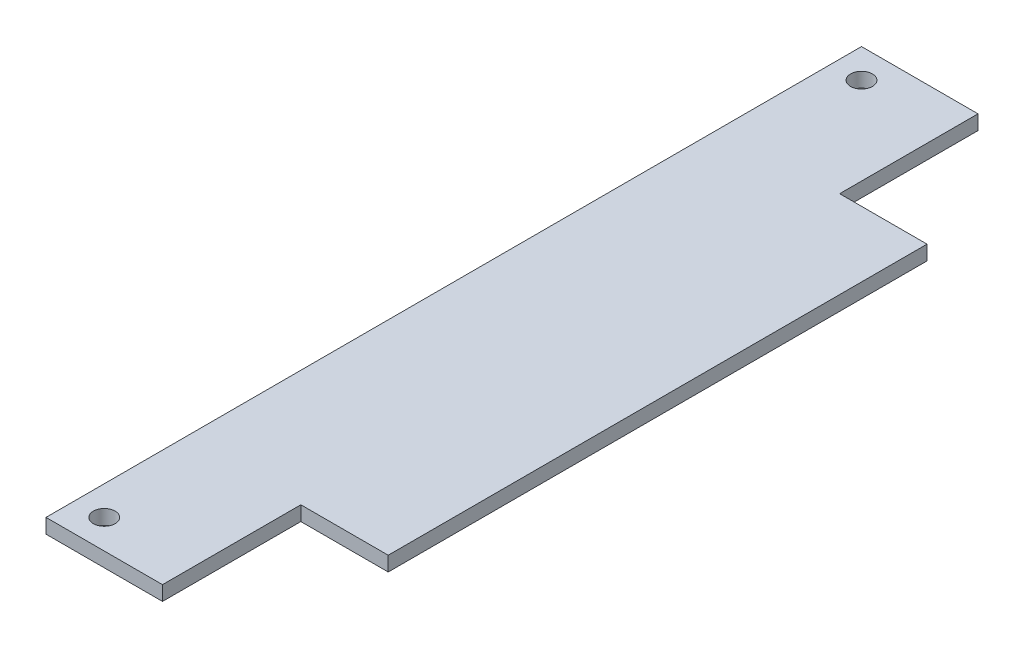
SolidWorks part; units mm, degrees
ref_plane "Front Plane" through (0, 0, 0) normal (0, 0, 1) x (1, 0, 0)
ref_plane "Top Plane" through (0, 0, 0) normal (0, 1, 0) x (1, 0, 0)
ref_plane "Right Plane" through (0, 0, 0) normal (1, 0, 0) x (0, 0, -1)
sketch "Sketch1" plane through (0, 0, 0) normal (0, 1, 0) x (1, 0, 0)
  line L0 (0, -177.8) -> (0, 177.8)
  line L1 (0, 177.8) -> (38.1, 177.8)
  line L2 (38.1, 177.8) -> (38.1, -177.8)
  line L3 (38.1, -177.8) -> (0, -177.8)
  line L4 (38.1, -38.1) -> (203.2, -38.1)
  line L5 (203.2, -38.1) -> (203.2, 38.1)
  line L6 (203.2, 38.1) -> (38.1, 38.1)
  line L7 (38.1, 38.1) -> (38.1, -38.1)
  line L8 (0, 0) -> (203.2, 0) construction
  dimension "D1" = 203.2
  dimension "D2" = 355.6
  dimension "D3" = 38.1
  dimension "D4" = 76.2
extrude "Boss-Extrude1" add sketch "Sketch1" along normal mid plane 6.35 contours L8 L0 L3 L2 L7 | L8 L7 L4 L5 | L2 L8 L5 L6 | L0 L8 L2 L1
hole_wizard "1/4 (0.25) Diameter Hole1" positions "Sketch2" profile "Sketch3" hole size "1/4" standard "ANSI Inch" end condition through all
sketch "Sketch2" plane through (0, 3.175, 0) normal (0, 1, 0) x (1, 0, 0)
  line L0 (203.2, 38.1) -> (38.1, 38.1) construction
  line L1 (38.1, -38.1) -> (203.2, -38.1) construction
  line L2 (203.2, -38.1) -> (203.2, 38.1) construction
  point P0 (190.5, 25.4)
  point P2 (190.5, -25.4)
  dimension "D1" = 12.7
  dimension "D2" = 12.7
  dimension "D3" = 12.7
sketch "Sketch3" plane through (190.5, 3.175, -25.4) normal (1, 0, 0) x (0, 0, 1)
  line L0 (0, 0) -> (0, 6.35)
  line L1 (0, 6.35) -> (3.9687, 6.35)
  line L2 (3.9687, 6.35) -> (3.9687, 0)
  line L5 (3.9687, 0) -> (0, 0)
  line L11 (0, -6.35) -> (0, 107.95) construction
  dimension "Thru Hole Dia." = 7.9375
  dimension "Thru Hole Depth" = 6.35
sketch "Sketch4" plane through (0, -3.175, 0) normal (0, -1, 0) x (1, 0, 0)
  line L0 (38.1, 177.8) -> (0, 177.8) construction
  line L8 (0, 177.8) -> (-50.8, 177.8)
  line L9 (-50.8, 177.8) -> (-50.8, -177.8)
  line L10 (-50.8, -177.8) -> (0, -177.8)
  line L11 (0, -177.8) -> (0, 177.8)
  circle A1 centre (-38.1, -165.1) radius 4.7625
  circle A3 centre (-38.1, 165.1) radius 4.7625
  dimension "D4" = 9.525
  dimension "D7" = 9.525
  dimension "D1" = 50.8
  dimension "D2" = 12.7
  dimension "D3" = 12.7
  dimension "D5" = 12.7
  dimension "D6" = 12.7
extrude "Boss-Extrude2" add sketch "Sketch4" against normal blind 6.35
sketch "Sketch5" plane through (0, -3.175, 0) normal (0, -1, 0) x (1, 0, 0)
  line L1 (38.1, 38.1) -> (203.2, 38.1)
  line L2 (38.1, 38.1) -> (38.1, -38.1)
  line L3 (38.1, -38.1) -> (203.2, -38.1)
  line L4 (203.2, 38.1) -> (203.2, -38.1)
extrude "Cut-Extrude1" cut sketch "Sketch5" against normal through all
sketch "Sketch6" plane through (0, -3.175, 0) normal (0, -1, 0) x (1, 0, 0)
  line L1 (38.1, 177.8) -> (0, 177.8)
  line L2 (38.1, 177.8) -> (38.1, 117.475)
  line L3 (38.1, 117.475) -> (0, 117.475)
  line L4 (0, 177.8) -> (0, 117.475)
  line L5 (38.1, -177.8) -> (0, -177.8)
  line L6 (38.1, -177.8) -> (38.1, -117.475)
  line L7 (38.1, -117.475) -> (0, -117.475)
  line L8 (0, -177.8) -> (0, -117.475)
  dimension "D1" = 234.95
  dimension "D2" = 38.1
extrude "Cut-Extrude2" cut sketch "Sketch6" against normal through all
